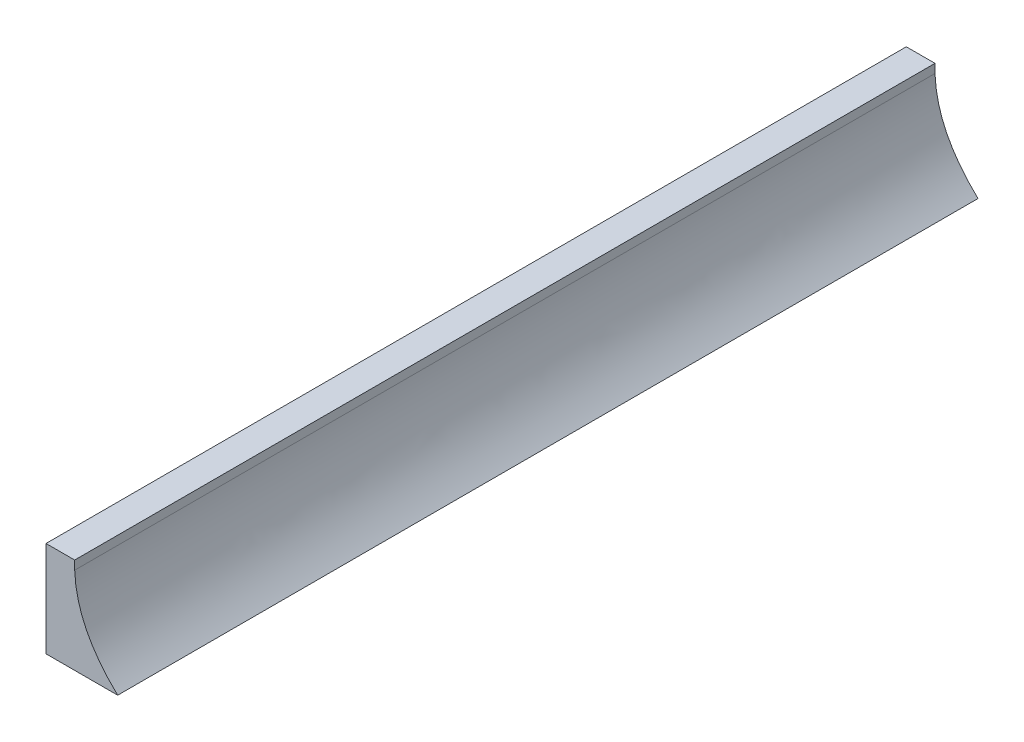
SolidWorks part; units mm, degrees
ref_plane "Plan de face" through (0, 0, 0) normal (0, 0, 1) x (1, 0, 0)
ref_plane "Plan de dessus" through (0, 0, 0) normal (0, 1, 0) x (1, 0, 0)
ref_plane "Plan de droite" through (0, 0, 0) normal (1, 0, 0) x (0, 0, -1)
sketch "Esquisse1" plane through (0, 0, 0) normal (0, 0, 1) x (1, 0, 0)
  line L0 (0, 0) -> (9, 0)
  line L1 (0, 0) -> (-6, 0)
  line L2 (0, 18.1549) -> (0, 20)
  line L3 (0, 20) -> (-6, 20)
  line L4 (-6, 0) -> (-6, 20)
  spline S0 degree 2 poles (0, 18.1549) (0.3756, 8.1113) (9, 0) knots 0.083456 0.083456 0.083456 1 1 1
  dimension "D1" = 20
  dimension "D2" = 6
  dimension "D3" = 9
extrude "Boss.-Extru.1" add sketch "Esquisse1" along normal blind 180
sketch "Esquisse2" plane through (-6, 0, 0) normal (-1, 0, 0) x (0, 0, 1)
  line L0 (180, 0) -> (0, 0) construction
  line L1 (40, 0) -> (70, 0)
  line L2 (40, 0) -> (40, 6)
  line L3 (40, 6) -> (70, 6)
  line L4 (70, 0) -> (70, 6)
  line L6 (110, 0) -> (140, 0)
  line L7 (110, 0) -> (110, 6)
  line L8 (110, 6) -> (140, 6)
  line L9 (140, 0) -> (140, 6)
  line L10 (0, 20) -> (0, 0) construction
  line L11 (180, 20) -> (180, 0) construction
  dimension "D1" = 6
  dimension "D2" = 30
  dimension "D3" = 30
  dimension "D4" = 40
  dimension "D5" = 40
  dimension "D6" = 6
extrude "Enlèv. mat.-Extru.1" cut sketch "Esquisse2" against normal blind 6
